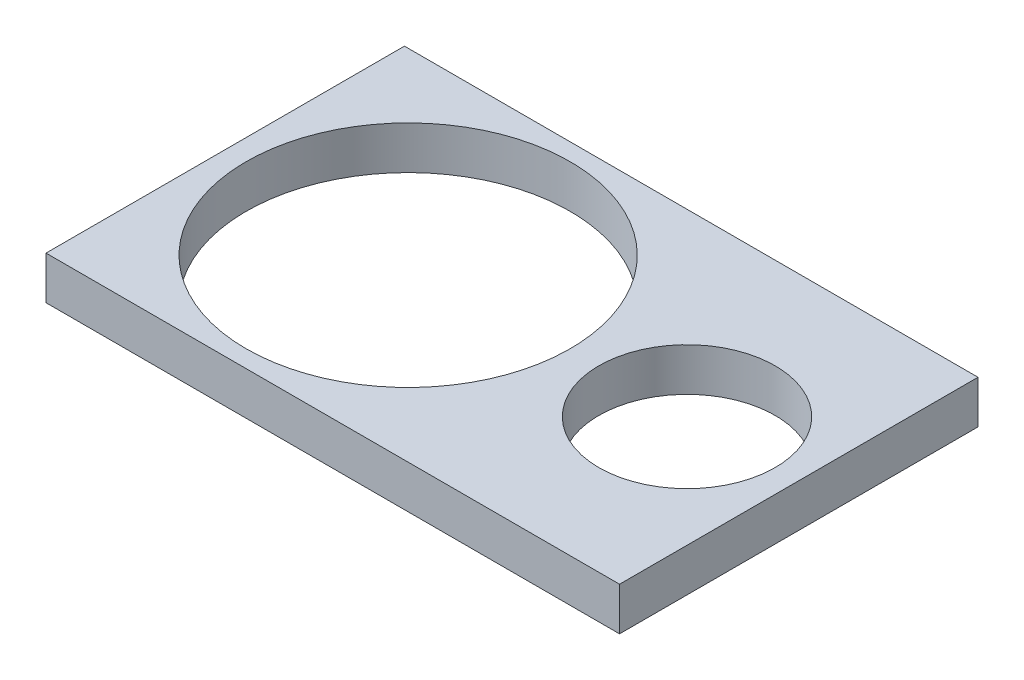
SolidWorks part; units mm, degrees
ref_plane "Front Plane" through (0, 0, 0) normal (0, 0, 1) x (1, 0, 0)
ref_plane "Top Plane" through (0, 0, 0) normal (0, 1, 0) x (1, 0, 0)
ref_plane "Right Plane" through (0, 0, 0) normal (1, 0, 0) x (0, 0, -1)
sketch "Sketch1" plane through (0, 0, 0) normal (0, 1, 0) x (1, 0, 0)
  line L1 (-20, -12.5) -> (20, -12.5)
  line L2 (-20, -12.5) -> (-20, 12.5)
  line L3 (-20, 12.5) -> (20, 12.5)
  line L4 (20, -12.5) -> (20, 12.5)
  line L5 (-20, -12.5) -> (20, 12.5) construction
  line L6 (-20, 12.5) -> (20, -12.5) construction
  point P0 (0, 0)
  dimension "D1" = 40
  dimension "D2" = 25
extrude "Boss-Extrude1" add sketch "Sketch1" along normal blind 3
sketch "Sketch2" plane through (0, 3, 0) normal (0, 1, 0) x (1, 0, 0)
  circle A0 centre (-7.2441, 0) radius 11.3
  circle A1 centre (12.2339, -0.0287) radius 6.15
  dimension "D1" = 22.6
  dimension "D2" = 12.3
extrude "Cut-Extrude1" cut sketch "Sketch2" against normal through all
